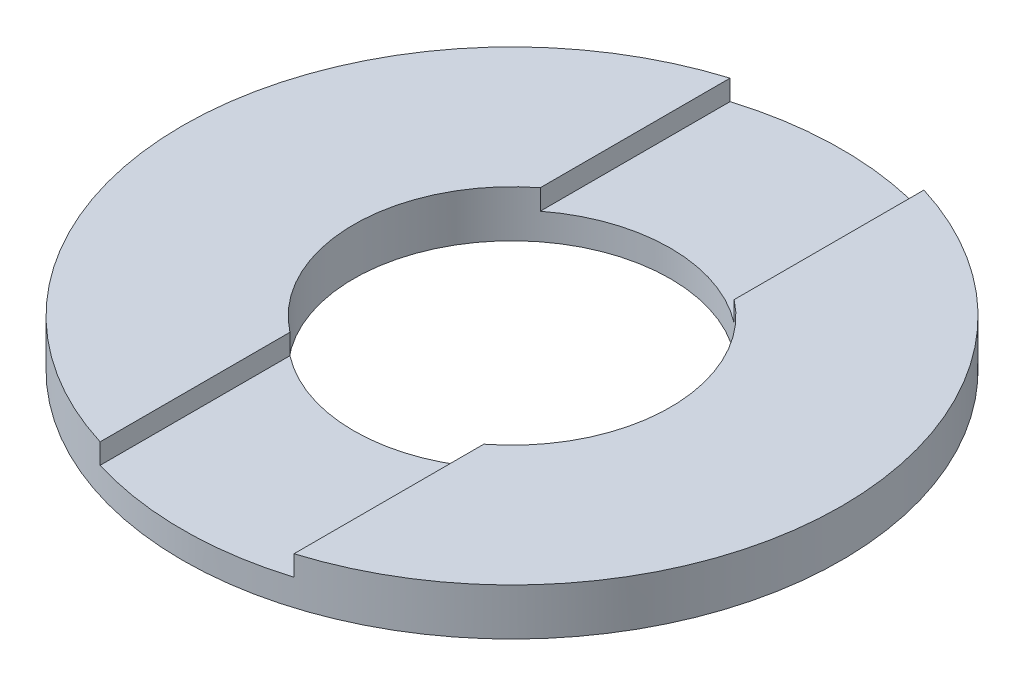
SolidWorks part; units mm, degrees
material "1023 Karbon Çeliği Levha (SS)"
ref_plane "Ön Düzlem" through (0, 0, 0) normal (0, 0, 1) x (1, 0, 0)
ref_plane "Üst Düzlem" through (0, 0, 0) normal (0, 1, 0) x (1, 0, 0)
ref_plane "Sağ Düzlem" through (0, 0, 0) normal (1, 0, 0) x (0, 0, -1)
sketch "Çizim1" plane through (0, 0, 0) normal (0, 1, 0) x (1, 0, 0)
  circle A0 centre (0, 0) radius 40.8
extrude "Yükseklik-Ekstrüzyon1" add sketch "Çizim1" along normal blind 2.9
sketch "Çizim2" plane through (0, 2.9, 0) normal (0, 1, 0) x (1, 0, 0)
  circle A0 centre (0, 0) radius 9.8
extrude "Kes-Ekstrüzyon1" cut sketch "Çizim2" against normal blind 7.9 and the other way blind 16
sketch "Çizim3" plane through (0, 2.9, 0) normal (0, 1, 0) x (1, 0, 0)
  line L1 (6, 0) -> (6, 43.1374)
  line L3 (-6, 0) -> (-6, 43.1374)
  line L4 (-6, 43.1374) -> (6, 43.1374)
  line L5 (6, 0) -> (6, -43.9269)
  line L6 (6, -43.9269) -> (-6, -43.9269)
  line L7 (-6, -43.9269) -> (-6, 0)
extrude "Kes-Ekstrüzyon2" cut sketch "Çizim3" against normal blind 1.26
sketch "Çizim4" plane through (0, 2.9, 0) normal (0, 1, 0) x (1, 0, 0)
  circle A0 centre (0, 0) radius 20.4
  circle A1 centre (0, 0) radius 40.8
extrude "Kes-Ekstrüzyon3" cut sketch "Çizim4" against normal blind 18.26 and the other way blind 21
